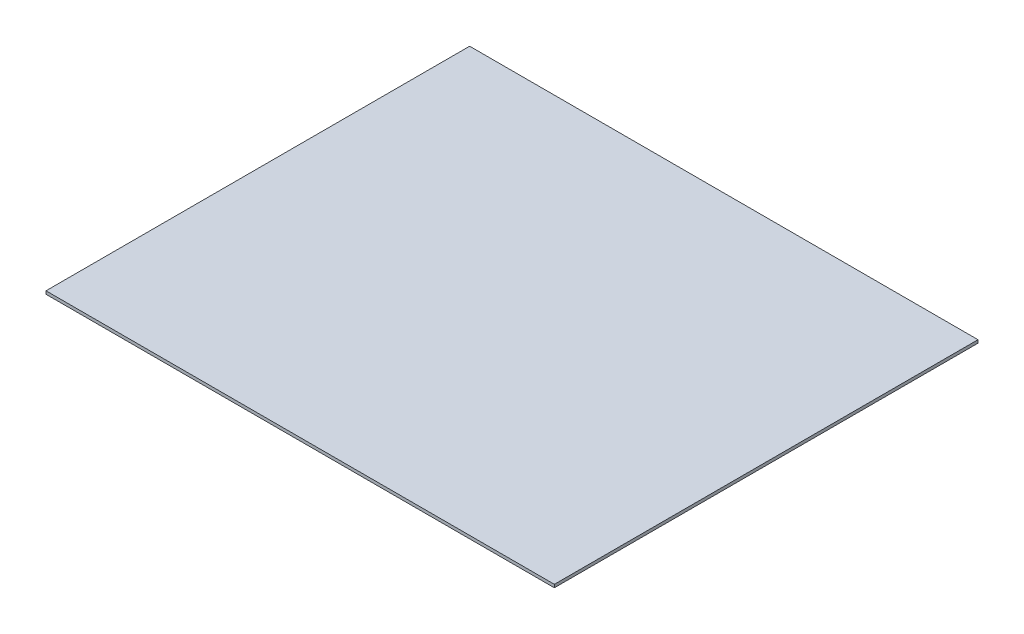
SolidWorks part; units mm, degrees
ref_plane "Front Plane" through (0, 0, 0) normal (0, 0, 1) x (1, 0, 0)
ref_plane "Top Plane" through (0, 0, 0) normal (0, 1, 0) x (1, 0, 0)
ref_plane "Right Plane" through (0, 0, 0) normal (1, 0, 0) x (0, 0, -1)
sketch "Sketch1" plane through (0, 0, 0) normal (0, 1, 0) x (1, 0, 0)
  line L1 (0, 0) -> (152.4, 0)
  line L2 (0, 0) -> (0, 127)
  line L3 (0, 127) -> (152.4, 127)
  line L4 (152.4, 0) -> (152.4, 127)
  dimension "D1" = 152.4
  dimension "D2" = 127
extrude "Boss-Extrude1" add sketch "Sketch1" along normal blind 0.9119
